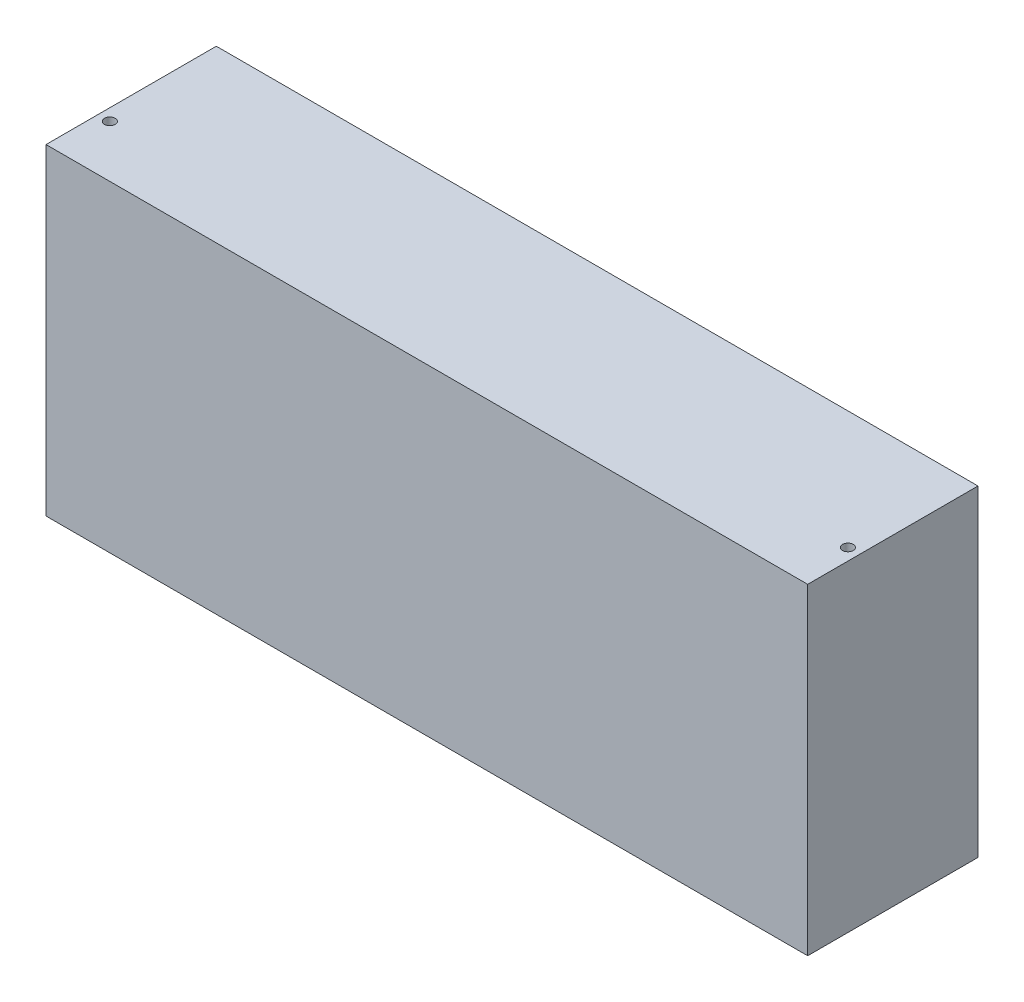
SolidWorks part; units mm, degrees
ref_plane "Front Plane" through (0, 0, 0) normal (0, 0, 1) x (1, 0, 0)
ref_plane "Top Plane" through (0, 0, 0) normal (0, 1, 0) x (1, 0, 0)
ref_plane "Right Plane" through (0, 0, 0) normal (1, 0, 0) x (0, 0, -1)
sketch "Sketch1" plane through (0, 0, 0) normal (0, 1, 0) x (1, 0, 0)
  line L0 (0, 0) -> (0, 18) construction
  line L1 (-80.5, 18) -> (80.5, 18)
  line L2 (-80.5, 18) -> (-80.5, -18)
  line L3 (-80.5, -18) -> (80.5, -18)
  line L4 (80.5, 18) -> (80.5, -18)
  line L5 (-80.5, 18) -> (80.5, -18) construction
  line L6 (-80.5, -18) -> (80.5, 18) construction
  circle A0 centre (78, -7) radius 1.1303
  circle A1 centre (-78, -7) radius 1.1303
  point P0 (0, 0)
  dimension "D3" = 2.2606
  dimension "D1" = 161
  dimension "D2" = 36
  dimension "D4" = 2.5
  dimension "D5" = 25
extrude "Boss-Extrude1" add sketch "Sketch1" along normal blind 68
